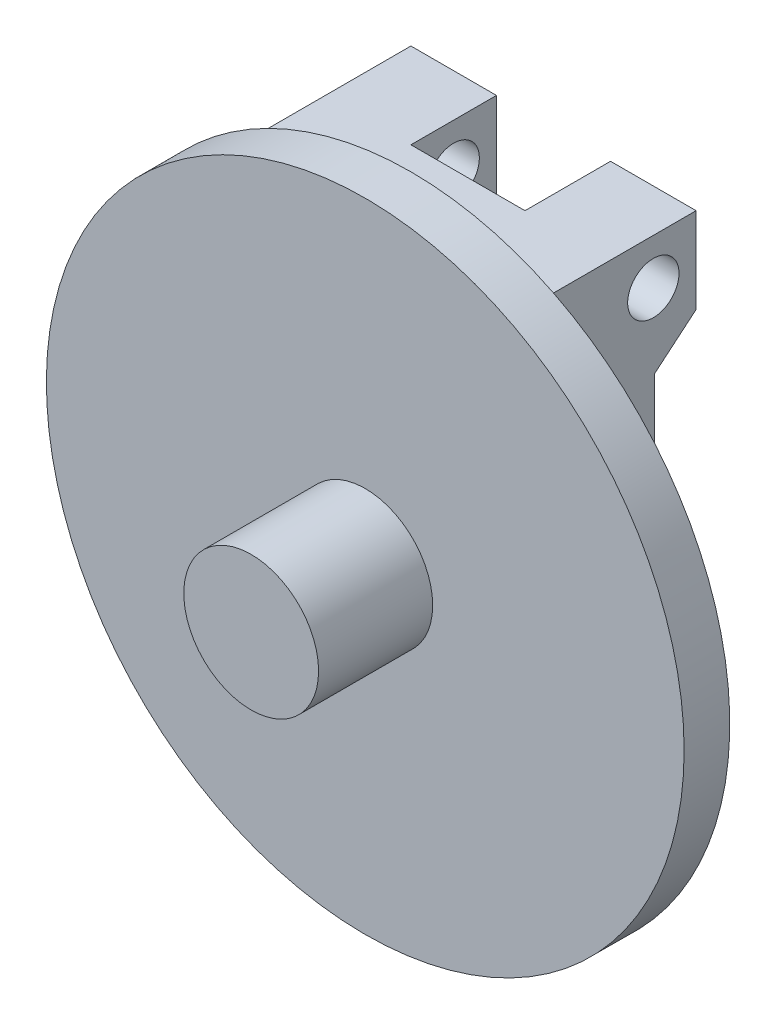
SolidWorks part; units mm, degrees
ref_plane "Front Plane" through (0, 0, 0) normal (0, 0, 1) x (1, 0, 0)
ref_plane "Top Plane" through (0, 0, 0) normal (0, 1, 0) x (1, 0, 0)
ref_plane "Right Plane" through (0, 0, 0) normal (1, 0, 0) x (0, 0, -1)
sketch "Sketch1" plane through (0, 0, 0) normal (0, 0, 1) x (1, 0, 0)
  line L1 (25, -50) -> (-25, -50)
  line L2 (25, -50) -> (25, 50)
  line L3 (25, 50) -> (-25, 50)
  line L4 (-25, -50) -> (-25, 50)
  line L5 (25, -50) -> (-25, 50) construction
  line L6 (25, 50) -> (-25, -50) construction
  point P0 (0, 0)
  dimension "D1" = 100
  dimension "D2" = 50
extrude "Boss-Extrude1" add sketch "Sketch1" along normal blind 10
sketch "Sketch10" plane through (25, 0, 0) normal (1, 0, 0) x (0, 0, -1)
  line L0 (0, 50) -> (15, 50)
  line L1 (15, 50) -> (15, 35)
  line L2 (15, 35) -> (7.6852, 28.8622)
  line L3 (7.6852, 28.8622) -> (7.6852, -28.8622)
  line L4 (7.6852, -28.8622) -> (15, -35)
  line L5 (15, -35) -> (15, -50)
  line L6 (15, -50) -> (0, -50)
  line L7 (0, -50) -> (0, 50)
  circle A0 centre (7.5, 42) radius 4.5
  circle A1 centre (7.6852, -42) radius 4.5
  dimension "D7" = 9
  dimension "D10" = 9
  dimension "D1" = 15
  dimension "D2" = 15
  dimension "D3" = 15
  dimension "D4" = 15
  dimension "D5" = 130
  dimension "D6" = 130
  dimension "D8" = 8
  dimension "D9" = 8
extrude "Boss-Extrude2" add sketch "Sketch10" against normal blind 15
mirror "Mirror1" about plane through (0, 0, 0) normal (1, 0, 0) of "Boss-Extrude2"
sketch "Sketch11" plane through (0, 0, 10) normal (0, 0, 1) x (1, 0, 0)
  circle A0 centre (0, 0) radius 55.9017
extrude "Boss-Extrude3" add sketch "Sketch11" along normal blind 8
sketch "Sketch12" plane through (0, 0, 18) normal (0, 0, 1) x (1, 0, 0)
  circle A0 centre (0, 0) radius 26.7379 construction
  circle A1 centre (0, 26.7379) radius 4.2394
  circle A2 centre (0, 0) radius 4.9969
sketch "Sketch13" plane through (0, 0, 18) normal (0, 0, 1) x (1, 0, 0)
  circle A0 centre (0, 0) radius 11.8172
extrude "Boss-Extrude4" add sketch "Sketch13" along normal blind 20 contours A0
